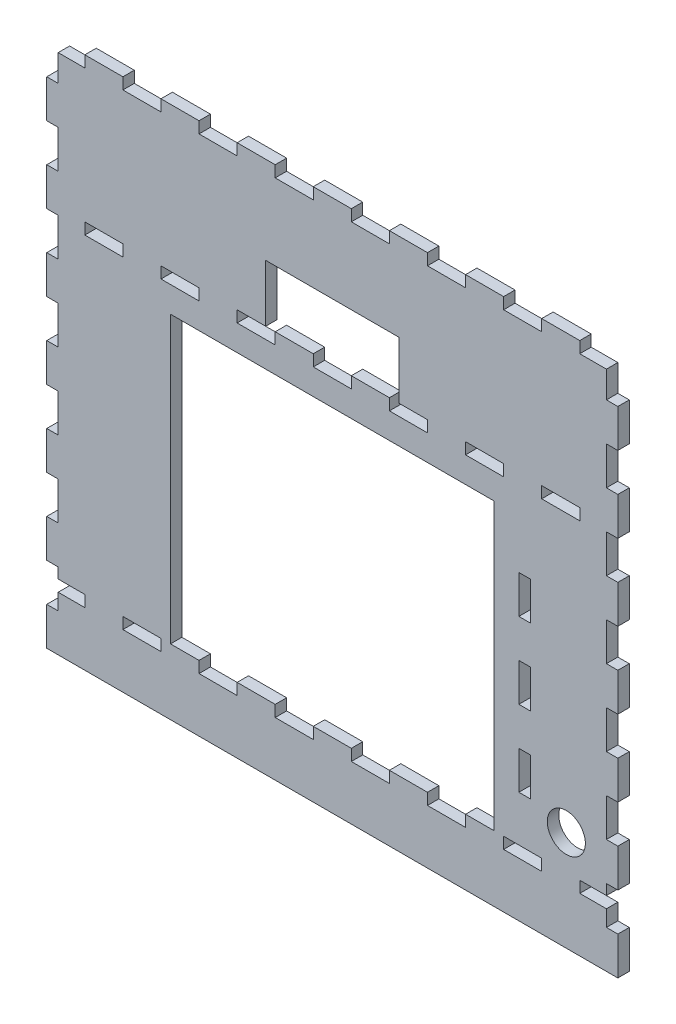
SolidWorks part; units mm, degrees
ref_plane "Alzado" through (0, 0, 0) normal (0, 0, 1) x (1, 0, 0)
ref_plane "Planta" through (0, 0, 0) normal (0, 1, 0) x (1, 0, 0)
ref_plane "Vista lateral" through (0, 0, 0) normal (1, 0, 0) x (0, 0, -1)
sketch "Croquis1" plane through (0, 0, 0) normal (0, 0, 1) x (1, 0, 0)
  line L0 (-45, 71.5) -> (-45, 68.5)
  line L1 (-72, -68.5) -> (72, -68.5)
  line L2 (-72, -58.5) -> (-72, -48.5)
  line L3 (-72, 68.5) -> (-65, 68.5)
  line L4 (72, -58.5) -> (72, -48.5)
  line L5 (-72, -68.5) -> (72, 68.5) construction
  line L6 (-72, 68.5) -> (72, -68.5) construction
  line L7 (-65, 71.5) -> (-55, 71.5)
  line L8 (-65, 71.5) -> (-65, 68.5)
  line L10 (-55, 71.5) -> (-55, 68.5)
  line L11 (-45, 71.5) -> (-35, 71.5)
  line L12 (-35, 71.5) -> (-35, 68.5)
  line L14 (-25, 71.5) -> (-25, 68.5)
  line L15 (-25, 71.5) -> (-15, 71.5)
  line L16 (-15, 71.5) -> (-15, 68.5)
  line L18 (-5, 71.5) -> (-5, 68.5)
  line L19 (-5, 71.5) -> (5, 71.5)
  line L20 (5, 71.5) -> (5, 68.5)
  line L22 (15, 71.5) -> (15, 68.5)
  line L23 (15, 71.5) -> (25, 71.5)
  line L24 (25, 71.5) -> (25, 68.5)
  line L26 (35, 71.5) -> (35, 68.5)
  line L27 (35, 71.5) -> (45, 71.5)
  line L28 (45, 71.5) -> (45, 68.5)
  line L30 (55, 71.5) -> (55, 68.5)
  line L31 (55, 71.5) -> (65, 71.5)
  line L32 (65, 71.5) -> (65, 68.5)
  line L35 (-72, 61.5) -> (-75, 61.5)
  line L37 (-72, 51.5) -> (-75, 51.5)
  line L38 (-75, 61.5) -> (-75, 51.5)
  line L58 (0, 0) -> (0, 41.2276) construction
  line L83 (-55, -51.25) -> (-55, -54.25)
  line L84 (-75, -51.25) -> (-65, -51.25)
  line L85 (-75, -51.25) -> (-75, -54.25)
  line L86 (-75, -54.25) -> (-65, -54.25)
  line L87 (-65, -51.25) -> (-65, -54.25)
  line L88 (-55, -51.25) -> (-45, -51.25)
  line L89 (-45, -51.25) -> (-45, -54.25)
  line L90 (-55, -54.25) -> (-45, -54.25)
  line L91 (-35, -51.25) -> (-35, -54.25)
  line L92 (-35, -51.25) -> (-25, -51.25)
  line L93 (-25, -51.25) -> (-25, -54.25)
  line L94 (-35, -54.25) -> (-25, -54.25)
  line L95 (-15, -51.25) -> (-15, -54.25)
  line L96 (-15, -51.25) -> (-5, -51.25)
  line L97 (-5, -51.25) -> (-5, -54.25)
  line L98 (-15, -54.25) -> (-5, -54.25)
  line L99 (5, -51.25) -> (5, -54.25)
  line L100 (5, -51.25) -> (15, -51.25)
  line L101 (15, -51.25) -> (15, -54.25)
  line L102 (5, -54.25) -> (15, -54.25)
  line L103 (25, -51.25) -> (25, -54.25)
  line L104 (25, -51.25) -> (35, -51.25)
  line L105 (35, -51.25) -> (35, -54.25)
  line L106 (25, -54.25) -> (35, -54.25)
  line L107 (45, -51.25) -> (45, -54.25)
  line L108 (45, -51.25) -> (55, -51.25)
  line L109 (55, -51.25) -> (55, -54.25)
  line L110 (45, -54.25) -> (55, -54.25)
  line L111 (65, -51.25) -> (65, -54.25)
  line L112 (65, -51.25) -> (75, -51.25)
  line L113 (75, -51.25) -> (75, -54.25)
  line L114 (65, -54.25) -> (75, -54.25)
  line L115 (-45, 33.5) -> (-45, 30.5)
  line L116 (-65, 33.5) -> (-55, 33.5)
  line L117 (-65, 33.5) -> (-65, 30.5)
  line L118 (-65, 30.5) -> (-55, 30.5)
  line L119 (-55, 33.5) -> (-55, 30.5)
  line L120 (-45, 33.5) -> (-35, 33.5)
  line L121 (-35, 33.5) -> (-35, 30.5)
  line L122 (-45, 30.5) -> (-35, 30.5)
  line L123 (-25, 33.5) -> (-25, 30.5)
  line L124 (-25, 33.5) -> (-15, 33.5)
  line L125 (-15, 33.5) -> (-15, 30.5)
  line L126 (-25, 30.5) -> (-15, 30.5)
  line L127 (-5, 33.5) -> (-5, 30.5)
  line L128 (-5, 33.5) -> (5, 33.5)
  line L129 (5, 33.5) -> (5, 30.5)
  line L130 (-5, 30.5) -> (5, 30.5)
  line L131 (15, 33.5) -> (15, 30.5)
  line L132 (15, 33.5) -> (25, 33.5)
  line L133 (25, 33.5) -> (25, 30.5)
  line L134 (15, 30.5) -> (25, 30.5)
  line L135 (35, 33.5) -> (35, 30.5)
  line L136 (35, 33.5) -> (45, 33.5)
  line L137 (45, 33.5) -> (45, 30.5)
  line L138 (35, 30.5) -> (45, 30.5)
  line L139 (55, 33.5) -> (55, 30.5)
  line L140 (55, 33.5) -> (65, 33.5)
  line L141 (65, 33.5) -> (65, 30.5)
  line L142 (55, 30.5) -> (65, 30.5)
  line L144 (-17.5, 48.5) -> (17.5, 48.5)
  line L145 (-17.5, 48.5) -> (-17.5, 33.5)
  line L146 (-17.5, 33.5) -> (17.5, 33.5)
  line L147 (17.5, 48.5) -> (17.5, 33.5)
  line L148 (-17.5, 48.5) -> (17.5, 33.5) construction
  line L149 (-17.5, 33.5) -> (17.5, 48.5) construction
  line L174 (-72, 41.5) -> (-75, 41.5)
  line L175 (-75, 41.5) -> (-75, 31.5)
  line L176 (-72, 31.5) -> (-75, 31.5)
  line L178 (-72, 21.5) -> (-75, 21.5)
  line L179 (-75, 21.5) -> (-75, 11.5)
  line L180 (-72, 11.5) -> (-75, 11.5)
  line L182 (-72, 1.5) -> (-75, 1.5)
  line L183 (-75, 1.5) -> (-75, -8.5)
  line L184 (-72, -8.5) -> (-75, -8.5)
  line L186 (-72, -18.5) -> (-75, -18.5)
  line L187 (-75, -18.5) -> (-75, -28.5)
  line L188 (-72, -28.5) -> (-75, -28.5)
  line L190 (-72, -38.5) -> (-75, -38.5)
  line L191 (-75, -38.5) -> (-75, -48.5)
  line L192 (-72, -48.5) -> (-75, -48.5)
  line L194 (-72, -58.5) -> (-75, -58.5)
  line L195 (-75, -58.5) -> (-75, -68.5)
  line L196 (-72, -68.5) -> (-75, -68.5)
  line L197 (72, -58.5) -> (75, -58.5)
  line L198 (75, -58.5) -> (75, -68.5)
  line L199 (72, -68.5) -> (75, -68.5)
  line L201 (72, -38.5) -> (75, -38.5)
  line L202 (75, -38.5) -> (75, -48.5)
  line L203 (72, -48.5) -> (75, -48.5)
  line L205 (72, -18.5) -> (75, -18.5)
  line L206 (75, -18.5) -> (75, -28.5)
  line L207 (72, -28.5) -> (75, -28.5)
  line L209 (72, 1.5) -> (75, 1.5)
  line L210 (75, 1.5) -> (75, -8.5)
  line L211 (72, -8.5) -> (75, -8.5)
  line L213 (72, 21.5) -> (75, 21.5)
  line L214 (75, 21.5) -> (75, 11.5)
  line L215 (72, 11.5) -> (75, 11.5)
  line L217 (72, 41.5) -> (75, 41.5)
  line L218 (75, 41.5) -> (75, 31.5)
  line L219 (72, 31.5) -> (75, 31.5)
  line L221 (72, 51.5) -> (75, 51.5)
  line L222 (75, 61.5) -> (75, 51.5)
  line L223 (72, 61.5) -> (75, 61.5)
  line L225 (-55, 68.5) -> (-45, 68.5)
  line L226 (-42.5, 23.75) -> (42.5, 23.75)
  line L227 (-42.5, 23.75) -> (-42.5, -51.25)
  line L228 (-42.5, -51.25) -> (42.5, -51.25)
  line L229 (42.5, 23.75) -> (42.5, -51.25)
  line L230 (-42.5, 23.75) -> (42.5, -51.25) construction
  line L231 (-42.5, -51.25) -> (42.5, 23.75) construction
  line L232 (-35, 68.5) -> (-25, 68.5)
  line L233 (-15, 68.5) -> (-5, 68.5)
  line L234 (5, 68.5) -> (15, 68.5)
  line L235 (25, 68.5) -> (35, 68.5)
  line L236 (45, 68.5) -> (55, 68.5)
  line L237 (65, 68.5) -> (72, 68.5)
  line L238 (72, 61.5) -> (72, 68.5)
  line L239 (72, 41.5) -> (72, 51.5)
  line L240 (72, 21.5) -> (72, 31.5)
  line L241 (72, 1.5) -> (72, 11.5)
  line L242 (72, -18.5) -> (72, -8.5)
  line L243 (72, -38.5) -> (72, -28.5)
  line L244 (49, -19.25) -> (49, -9.25)
  line L245 (-72, -38.5) -> (-72, -28.5)
  line L246 (49, -39.25) -> (52, -39.25)
  line L247 (49, -39.25) -> (49, -29.25)
  line L248 (-72, -18.5) -> (-72, -8.5)
  line L249 (49, -29.25) -> (52, -29.25)
  line L250 (-72, 1.5) -> (-72, 11.5)
  line L251 (52, -39.25) -> (52, -29.25)
  line L252 (-72, 21.5) -> (-72, 31.5)
  line L253 (-72, 41.5) -> (-72, 51.5)
  line L254 (49, -19.25) -> (52, -19.25)
  line L255 (-72, 61.5) -> (-72, 68.5)
  line L256 (52, -19.25) -> (52, -9.25)
  line L257 (49, -9.25) -> (52, -9.25)
  line L258 (49, 0.75) -> (49, 10.75)
  line L259 (49, 0.75) -> (52, 0.75)
  line L260 (52, 0.75) -> (52, 10.75)
  line L261 (49, 10.75) -> (52, 10.75)
  circle A0 centre (61.4732, -42.1741) radius 5
  point P0 (0, 0)
  point P39 (-65, -52.75)
  point P120 (0, 41)
  point P157 (0, -13.75)
  point P165 (50.5, -19.25)
  point P176 (61.9118, -39.25)
  point P177 (0, 0)
  dimension "D35" = 10
  dimension "D1" = 144
  dimension "D2" = 137
  dimension "D3" = 10
  dimension "D4" = 3
  dimension "D5" = 7
  dimension "D7" = 10
  dimension "D8" = 75
  dimension "D9" = 3
  dimension "D10" = 10
  dimension "D12" = 10
  dimension "D13" = 10
  dimension "D14" = 3
  dimension "D16" = 14.25
  dimension "D17" = 10
  dimension "D18" = 10
  dimension "D19" = 3
  dimension "D20" = 7
  dimension "D22" = 10
  dimension "D23" = 35
  dimension "D24" = 15
  dimension "D25" = 35
  dimension "D26" = 7
  dimension "D27" = 85
  dimension "D28" = 2.75
  dimension "D29" = 10
  dimension "D30" = 3
  dimension "D31" = 6.5
  dimension "D33" = 12
  dimension "D34" = 10
  dimension "D6" = 7
  dimension "D15" = 8
  dimension "D21" = 7
  dimension "D11" = 7
  dimension "D32" = 3
extrude "Saliente-Extruir1" add sketch "Croquis1" along normal blind 3 contours L255 L35 L38 L37 L253 L174 L175 L176 L252 L178 L179 L180 L250 L182 L183 L184 L248 L186 L187 L188 L245 L190 L191 L192 L2 L84 L87 L86 L194 L195 L196 L1 L199 L198 L197 L4 L114 L111 L112 L203 L202 L201 L243 L207 L206 L205 L242 L211 L210
